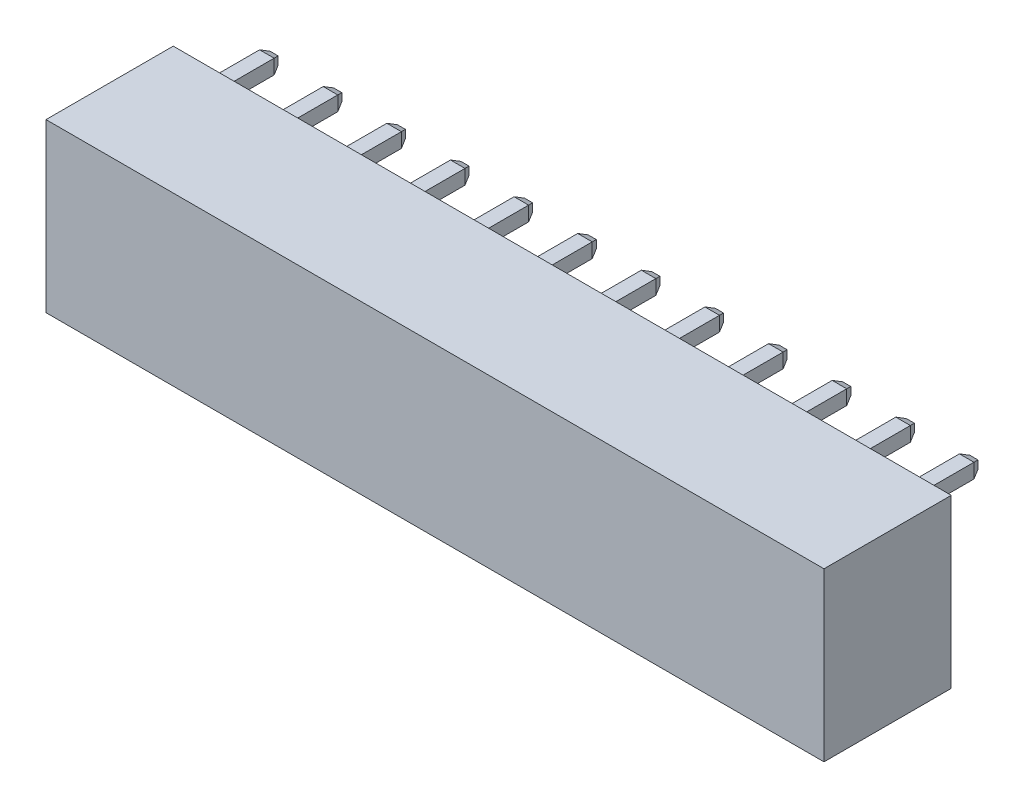
SolidWorks part; units mm, degrees
ref_plane "Спереди" through (0, 0, 0) normal (0, 0, 1) x (1, 0, 0)
ref_plane "Сверху" through (0, 0, 0) normal (0, 1, 0) x (1, 0, 0)
ref_plane "Справа" through (0, 0, 0) normal (1, 0, 0) x (0, 0, -1)
sketch "Эскиз1" plane through (0, 0, 0) normal (0, 0, 1) x (1, 0, 0)
  line L1 (21.4, 9.2) -> (-21.4, 9.2)
  line L2 (21.4, 9.2) -> (21.4, 0)
  line L3 (21.4, 0) -> (-21.4, 0)
  line L4 (-21.4, 9.2) -> (-21.4, 0)
  line L5 (21.4, 9.2) -> (-21.4, 0) construction
  line L6 (21.4, 0) -> (-21.4, 9.2) construction
  point P0 (0, 4.6)
  dimension "D1" = 9.2
  dimension "D2" = 42.8
extrude "Бобышка-Вытянуть1" add sketch "Эскиз1" along normal blind 7
sketch "Эскиз2" plane through (0, 0, 0) normal (0, 0, -1) x (-1, 0, 0)
  line L0 (21.4, 0) -> (-21.4, 0) construction
  line L1 (-19.65, 7.6) -> (-18.85, 7.6)
  line L2 (-19.65, 7.6) -> (-19.65, 8.4)
  line L3 (-19.65, 8.4) -> (-18.85, 8.4)
  line L4 (-18.85, 7.6) -> (-18.85, 8.4)
  line L5 (-19.65, 7.6) -> (-18.85, 8.4) construction
  line L6 (-19.65, 8.4) -> (-18.85, 7.6) construction
  line L7 (-21.4, 0) -> (-21.4, 9.2) construction
  point P0 (-19.25, 8)
  dimension "D1" = 8
  dimension "D2" = 0.8
  dimension "D3" = 2.15
extrude "Бобышка-Вытянуть2" add sketch "Эскиз2" along normal blind 3.4
chamfer "Фаска1" distance 0.4 angle 24 4 edges at (19.25, 8.4, -3.4) (18.85, 8, -3.4) (19.25, 7.6, -3.4) (19.65, 8, -3.4)
sketch "Эскиз3" plane through (0, 0, 0) normal (0, -1, 0) x (1, 0, 0)
  line L1 (17.65, 0.8) -> (20.75, 0.8)
  line L2 (17.65, 0.8) -> (17.65, 5)
  line L4 (20.75, 0.8) -> (20.75, 5)
  line L5 (17.65, 0.8) -> (20.75, 5) construction
  line L6 (17.65, 5) -> (20.75, 0.8) construction
  line L7 (-21.4, 0) -> (21.4, 0) construction
  line L9 (21.4, 7) -> (21.4, 0) construction
  line L10 (-21.4, 7) -> (21.4, 7) construction
  line L11 (17.65, 6.5) -> (20.75, 6.5)
  line L12 (17.65, 5) -> (18.65, 5)
  line L13 (18.65, 5) -> (17.65, 6.5)
  line L14 (20.75, 5) -> (19.75, 5)
  line L15 (19.75, 5) -> (20.75, 6.5)
  point P0 (19.2, 2.9)
  point P5 (19.2, 6.5)
  dimension "D1" = 2.2
  dimension "D2" = 0.8
  dimension "D3" = 2
  dimension "D4" = 3.1
  dimension "D5" = 0.5
  dimension "D6" = 1
extrude "Вырез-Вытянуть1" cut sketch "Эскиз3" against normal blind 7
pattern_linear "Линейный массив1" count 12 spacing 3.5 along (-1, 0, 0) of "Бобышка-Вытянуть2", "Фаска1"
pattern_linear "Линейный массив2" count 12 spacing 3.5 along (-1, 0, 0) of "Вырез-Вытянуть1"
sketch "Эскиз4" plane through (0, 7, 0) normal (0, -1, 0) x (1, 0, 0)
  line L0 (19.65, -3) -> (19.65, 0) construction
  line L1 (18.85, 3.4) -> (19.65, 3.4)
  line L2 (18.85, 3.4) -> (18.85, 2.6)
  line L3 (18.85, 2.6) -> (19.65, 2.6)
  line L4 (19.65, 3.4) -> (19.65, 2.6)
  line L5 (18.85, 3.4) -> (19.65, 2.6) construction
  line L6 (18.85, 2.6) -> (19.65, 3.4) construction
  line L7 (18.85, -3) -> (18.85, 0) construction
  line L8 (-21.4, 0) -> (21.4, 0) construction
  point P0 (19.25, 3)
  dimension "D1" = 3
extrude "Бобышка-Вытянуть3" add sketch "Эскиз4" along normal blind 6
chamfer "Фаска2" distance 0.4 angle 24 4 edges at (19.65, 1, 3) (19.25, 1, 3.4) (18.85, 1, 3) (19.25, 1, 2.6)
pattern_linear "Линейный массив3" count 12 spacing 3.5 along (-1, 0, 0) of "Фаска2", "Бобышка-Вытянуть3"
equation "\"n\"= 12"
equation "\"width\"= 3.5 * ( \"n\" - 1 ) + 4.3"
equation "\"D2@Эскиз1\" = 3.5 * ( \"n\" - 1 ) + 4.3"
equation "\"D1@Линейный массив1\"=\"n\""
equation "\"D1@Линейный массив2\"=\"n\""
equation "\"D1@Линейный массив3\"=\"n\""
